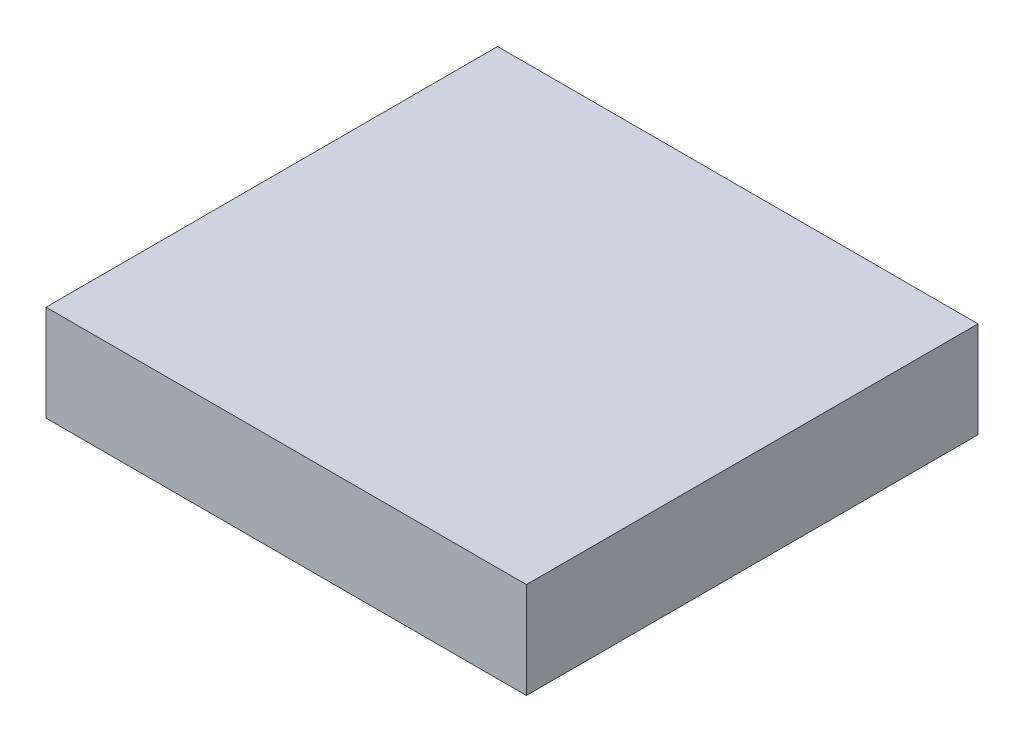
SolidWorks part; units mm, degrees
ref_plane "Front Plane" through (0, 0, 0) normal (0, 0, 1) x (1, 0, 0)
ref_plane "Top Plane" through (0, 0, 0) normal (0, 1, 0) x (1, 0, 0)
ref_plane "Right Plane" through (0, 0, 0) normal (1, 0, 0) x (0, 0, -1)
sketch "Sketch1" plane through (0, 0, 0) normal (0, 1, 0) x (1, 0, 0)
  line L1 (-50, 47) -> (50, 47)
  line L2 (-50, 47) -> (-50, -47)
  line L3 (-50, -47) -> (50, -47)
  line L4 (50, 47) -> (50, -47)
  line L5 (-50, 47) -> (50, -47) construction
  line L6 (-50, -47) -> (50, 47) construction
  point P0 (0, 0)
  dimension "D1" = 100
  dimension "D2" = 94
extrude "Boss-Extrude1" add sketch "Sketch1" along normal blind 20
